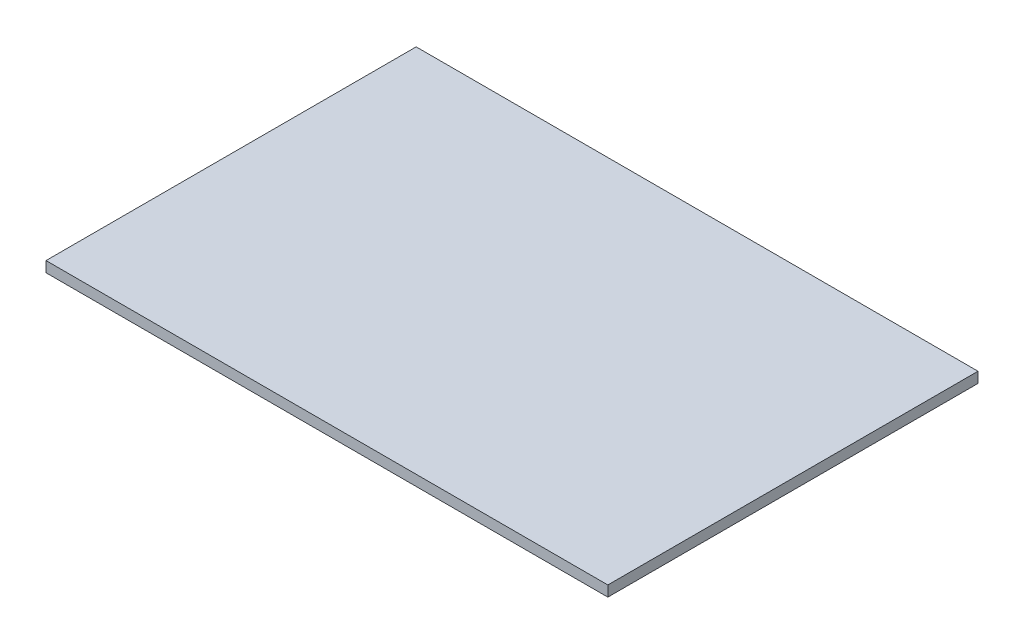
SolidWorks part; units mm, degrees
material "ABS PC"
ref_plane "Front Plane" through (0, 0, 0) normal (0, 0, 1) x (1, 0, 0)
ref_plane "Top Plane" through (0, 0, 0) normal (0, 1, 0) x (1, 0, 0)
ref_plane "Right Plane" through (0, 0, 0) normal (1, 0, 0) x (0, 0, -1)
sketch "Sketch1" plane through (0, 0, 0) normal (0, 1, 0) x (1, 0, 0)
  line L1 (85, 56) -> (0, 56)
  line L2 (85, 56) -> (85, 0)
  line L3 (85, 0) -> (0, 0)
  line L4 (0, 56) -> (0, 0)
  dimension "D1" = 85
  dimension "D2" = 56
extrude "Printplaat" add sketch "Sketch1" along normal blind 1.6
